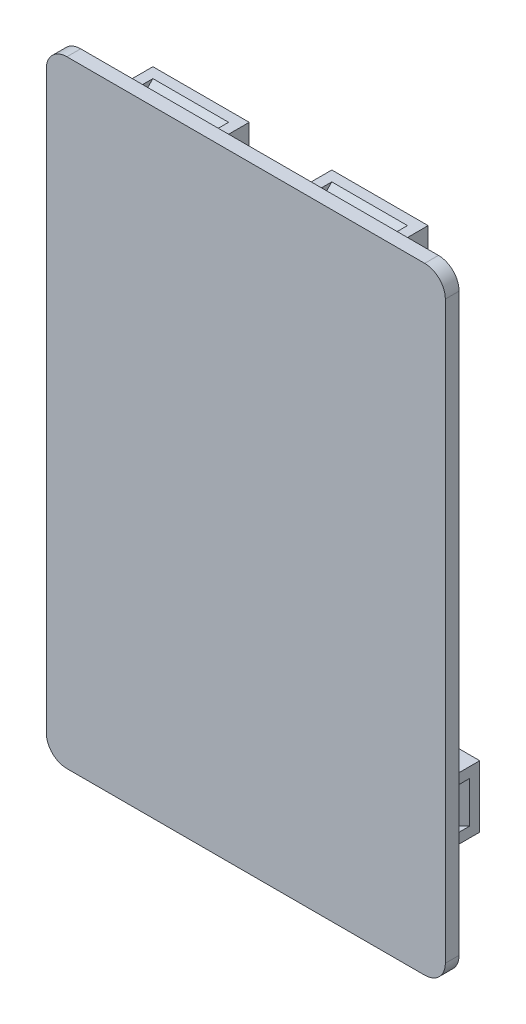
SolidWorks part; units mm, degrees
ref_plane "前视基准面" through (0, 0, 0) normal (0, 0, 1) x (1, 0, 0)
ref_plane "上视基准面" through (0, 0, 0) normal (0, 1, 0) x (1, 0, 0)
ref_plane "右视基准面" through (0, 0, 0) normal (1, 0, 0) x (0, 0, -1)
other "Configuration Table"
sketch "草图2" plane through (0, 0, 0) normal (0, 0, 1) x (1, 0, 0)
  line L4 (0, 86.6) -> (0, 3)
  line L5 (3, 0) -> (55, 0)
  line L6 (58, 3) -> (58, 86.6)
  line L7 (55, 89.6) -> (3, 89.6)
  line L8 (0, 86.6) -> (0, 3)
  line L9 (3, 0) -> (55, 0)
  line L10 (58, 3) -> (58, 86.6)
  line L11 (55, 89.6) -> (3, 89.6)
  arc A4 (3, 89.6) -> (0, 86.6) centre (3, 86.6) ccw
  arc A5 (0, 3) -> (3, 0) centre (3, 3) ccw
  arc A6 (55, 0) -> (58, 3) centre (55, 3) ccw
  arc A7 (58, 86.6) -> (55, 89.6) centre (55, 86.6) ccw
  arc A8 (3, 89.6) -> (0, 86.6) centre (3, 86.6) ccw
  arc A9 (0, 3) -> (3, 0) centre (3, 3) ccw
  arc A10 (55, 0) -> (58, 3) centre (55, 3) ccw
  arc A11 (58, 86.6) -> (55, 89.6) centre (55, 86.6) ccw
  dimension "D1" = 0
extrude "凸台-拉伸1" add sketch "草图2" along normal blind 2
ref_plane "基准面1" through (3, 89.6, 2) normal (-1, 0, 0) x (0, 0, 1)
sketch "草图4" plane through (0, 0, 0) normal (0, 0, -1) x (-1, 0, 0)
  line L0 (-29, 89.6) -> (-29, 0) construction
  line L4 (-3, 89.6) -> (-55, 89.6)
  line L5 (-58, 86.6) -> (-58, 3)
  line L6 (-55, 0) -> (-3, 0)
  line L7 (0, 3) -> (0, 86.6)
  line L8 (-3, 89.6) -> (-55, 89.6)
  line L9 (-58, 86.6) -> (-58, 3)
  line L10 (-55, 0) -> (-3, 0)
  line L11 (0, 3) -> (0, 86.6)
  line L17 (-47.5, 88.1) -> (-49, 88.1)
  line L26 (-36.5, 86.6) -> (-47.5, 86.6)
  line L27 (-36.5, 86.6) -> (-36.5, 88.1)
  line L28 (-36.5, 88.1) -> (-47.5, 88.1)
  line L29 (-47.5, 86.6) -> (-47.5, 88.1)
  line L34 (-49, 88.1) -> (-49, 85.1)
  line L35 (-49, 85.1) -> (-35, 85.1)
  line L36 (-35, 85.1) -> (-35, 88.1)
  line L37 (-35, 88.1) -> (-36.5, 88.1)
  line L38 (-10.5, 88.1) -> (-9, 88.1)
  line L39 (-9, 88.1) -> (-9, 85.1)
  line L40 (-9, 85.1) -> (-23, 85.1)
  line L41 (-23, 85.1) -> (-23, 88.1)
  line L42 (-23, 88.1) -> (-21.5, 88.1)
  line L43 (-21.5, 88.1) -> (-10.5, 88.1)
  arc A4 (0, 86.6) -> (-3, 89.6) centre (-3, 86.6) ccw
  arc A5 (-55, 89.6) -> (-58, 86.6) centre (-55, 86.6) ccw
  arc A6 (-58, 3) -> (-55, 0) centre (-55, 3) ccw
  arc A7 (-3, 0) -> (0, 3) centre (-3, 3) ccw
  arc A8 (0, 86.6) -> (-3, 89.6) centre (-3, 86.6) ccw
  arc A9 (-55, 89.6) -> (-58, 86.6) centre (-55, 86.6) ccw
  arc A10 (-58, 3) -> (-55, 0) centre (-55, 3) ccw
  arc A11 (-3, 0) -> (0, 3) centre (-3, 3) ccw
  dimension "D2" = 7.5
  dimension "D3" = 11
  dimension "D4" = 1.5
  dimension "D5" = 1.5
  dimension "D6" = 1.5
  dimension "D7" = 1.5
  dimension "D8" = 1.5
  dimension "D1" = 0
extrude "凸台-拉伸3" add sketch "草图4" along normal blind 4.5 contours L36 L37 L27 L26 L29 L17 L34 L35 | L43 L42 L41 L40 L39 L38 | L29 L26 L27 L28
sketch "草图5" plane through (49, 0, 0) normal (1, 0, 0) x (0, 0, -1)
  line L0 (1.5, 86.6) -> (1.5, 88.1) construction
  line L1 (3, 88.1) -> (3, 85.1)
  line L2 (3, 86.6) -> (0, 86.6)
  line L3 (1.5, 86.6) -> (0, 88.1)
  line L4 (0, 88.1) -> (0, 85.1)
  line L5 (0, 85.1) -> (4.5, 85.1)
  line L6 (4.5, 85.1) -> (4.5, 88.1)
  line L7 (4.5, 88.1) -> (0, 88.1)
  line L8 (0, 88.1) -> (0, 85.1)
  line L9 (0, 85.1) -> (4.5, 85.1)
  line L10 (4.5, 85.1) -> (4.5, 88.1)
  line L11 (4.5, 88.1) -> (0, 88.1)
  line L12 (3, 88.1) -> (1.5, 86.6)
  line M12 (4.5, 88.1) -> (0, 88.1)
  dimension "D3" = 1.5
  dimension "D1" = 0
extrude "切除-拉伸3" cut sketch "草图5" against normal blind 60 contours L0 L12 M12 | L3 L0 L11
sketch "草图6" plane through (0, 88.1, 0) normal (0, 1, 0) x (1, 0, 0)
  line L0 (35, 4.5) -> (35, 3) construction
  line L1 (35, 3) -> (35, 1.5) construction
  line L2 (35, 1.5) -> (35, 0) construction
  line L3 (49, 1.5) -> (49, 0) construction
  line L4 (49, 4.5) -> (49, 3) construction
  line L5 (49, 3) -> (49, 1.5) construction
  line L6 (35, 4.5) -> (49, 4.5) construction
  line L7 (55, 0) -> (3, 0) construction
  line L8 (9, 4.5) -> (9, 3) construction
  line L9 (23, 4.5) -> (9, 4.5) construction
  line L10 (23, 4.5) -> (23, 3) construction
  line L11 (23, 1.5) -> (23, 0) construction
  line L12 (23, 3) -> (23, 1.5) construction
  line L13 (9, 1.5) -> (9, 3) construction
  line L14 (9, 0) -> (9, 1.5) construction
  line L15 (35, 4.5) -> (35, 3)
  line L16 (35, 3) -> (35, 1.5)
  line L17 (35, 1.5) -> (35, 0)
  line L18 (49, 1.5) -> (49, 0)
  line L19 (49, 4.5) -> (49, 3)
  line L20 (49, 3) -> (49, 1.5)
  line L21 (35, 4.5) -> (49, 4.5)
  line L22 (55, 0) -> (3, 0)
  line L23 (9, 4.5) -> (9, 3)
  line L24 (23, 4.5) -> (9, 4.5)
  line L25 (23, 4.5) -> (23, 3)
  line L26 (23, 1.5) -> (23, 0)
  line L27 (23, 3) -> (23, 1.5)
  line L28 (9, 1.5) -> (9, 3)
  line L29 (9, 0) -> (9, 1.5)
  line L31 (9, 4.5) -> (10.5, 4.5)
  line L32 (9, 4.5) -> (9, 0)
  line L33 (9, 0) -> (10.5, 0)
  line L34 (10.5, 4.5) -> (10.5, 0)
  line L35 (23, 4.5) -> (21.5, 4.5)
  line L36 (23, 4.5) -> (23, 0)
  line L37 (23, 0) -> (21.5, 0)
  line L38 (21.5, 4.5) -> (21.5, 0)
  line L39 (35, 4.5) -> (36.5, 4.5)
  line L40 (35, 4.5) -> (35, 0)
  line L41 (35, 0) -> (36.5, 0)
  line L42 (36.5, 4.5) -> (36.5, 0)
  line L43 (49, 4.5) -> (47.5, 4.5)
  line L44 (49, 4.5) -> (49, 0)
  line L45 (49, 0) -> (47.5, 0)
  line L46 (47.5, 4.5) -> (47.5, 0)
  line M12 (35, 3) -> (49, 3)
  line M13 (49, 3) -> (49, 4.5)
  line M14 (49, 4.5) -> (35, 4.5)
  line M15 (35, 4.5) -> (35, 3)
  dimension "D1" = 1.5
  dimension "D2" = 1.5
  dimension "D3" = 1.5
  dimension "D4" = 1.5
extrude "凸台-拉伸4" add sketch "草图6" against normal blind 1.5 contours L34 L24 L23 L28 L29 L22 | L24 L38 L22 L26 L27 L25 | L42 L21 M15 M12 | L42 L16 L17 L22 M12 | L46 L22 L18 L20 M12 | L46 M14 M12 M13
sketch "草图8" plane through (0, 0, 0) normal (0, 0, -1) x (-1, 0, 0)
  line L0 (-56.5, 17) -> (-56.5, 15.5)
  line L1 (-55, 17) -> (-56.5, 17)
  line L2 (-55, 17) -> (-55, 23)
  line L3 (-55, 23) -> (-56.5, 23)
  line L4 (0, 3) -> (0, 86.6)
  line L5 (-3, 89.6) -> (-55, 89.6)
  line L6 (-58, 86.6) -> (-58, 3)
  line L7 (-55, 0) -> (-3, 0)
  line L8 (0, 3) -> (0, 86.6)
  line L9 (-3, 89.6) -> (-55, 89.6)
  line L10 (-58, 86.6) -> (-58, 3)
  line L11 (-55, 0) -> (-3, 0)
  line L12 (-56.5, 17) -> (-56.5, 23)
  line L17 (-56.5, 15.5) -> (-53.5, 15.5)
  line L18 (-53.5, 15.5) -> (-53.5, 24.5)
  line L19 (-53.5, 24.5) -> (-56.5, 24.5)
  line L20 (-56.5, 24.5) -> (-56.5, 23)
  line L21 (-29, 179.2) -> (-29, 0)
  line L22 (-1.5, 15.5) -> (-4.5, 15.5)
  line L23 (-1.5, 17) -> (-1.5, 15.5)
  line L24 (-1.5, 17) -> (-1.5, 23)
  line L25 (-1.5, 24.5) -> (-1.5, 23)
  line L26 (-4.5, 24.5) -> (-1.5, 24.5)
  line L27 (-4.5, 15.5) -> (-4.5, 24.5)
  arc A4 (0, 86.6) -> (-3, 89.6) centre (-3, 86.6) ccw
  arc A5 (-55, 89.6) -> (-58, 86.6) centre (-55, 86.6) ccw
  arc A6 (-58, 3) -> (-55, 0) centre (-55, 3) ccw
  arc A7 (-3, 0) -> (0, 3) centre (-3, 3) ccw
  arc A8 (0, 86.6) -> (-3, 89.6) centre (-3, 86.6) ccw
  arc A9 (-55, 89.6) -> (-58, 86.6) centre (-55, 86.6) ccw
  arc A10 (-58, 3) -> (-55, 0) centre (-55, 3) ccw
  arc A11 (-3, 0) -> (0, 3) centre (-3, 3) ccw
  point P23 (-29, 89.6)
  dimension "D2" = 17
  dimension "D3" = 6
  dimension "D4" = 1.5
  dimension "D5" = 1.5
  dimension "D6" = 1.5
  dimension "D7" = 1.5
  dimension "D8" = 1.5
  dimension "D1" = 0
extrude "凸台-拉伸5" add sketch "草图8" along normal blind 4.5 contours L19 L20 L3 L2 L1 L0 L17 L18 | L12 L1 L2 L3 | L27 L22 L23 L24 L25 L26
sketch "草图9" plane through (0, 15.5, 0) normal (0, -1, 0) x (1, 0, 0)
  line L0 (56.5, 0) -> (53.5, 0) construction
  line L1 (53.5, 0) -> (53.5, -4.5) construction
  line L2 (53.5, -4.5) -> (56.5, -4.5) construction
  line L3 (56.5, -4.5) -> (56.5, 0) construction
  line L4 (4.5, 0) -> (1.5, 0) construction
  line L5 (1.5, 0) -> (1.5, -4.5) construction
  line L6 (1.5, -4.5) -> (4.5, -4.5) construction
  line L7 (4.5, -4.5) -> (4.5, 0) construction
  line L8 (56.5, 0) -> (53.5, 0)
  line L9 (53.5, 0) -> (53.5, -4.5)
  line L10 (53.5, -4.5) -> (56.5, -4.5)
  line L11 (56.5, -4.5) -> (56.5, 0)
  line L12 (4.5, 0) -> (1.5, 0)
  line L13 (1.5, 0) -> (1.5, -4.5)
  line L14 (1.5, -4.5) -> (4.5, -4.5)
  line L15 (4.5, -4.5) -> (4.5, 0)
  line L16 (1.5, -3) -> (4.5, -3)
  line L17 (3, 0) -> (3, -3)
  line L18 (3, -1.5) -> (4.5, -1.5) construction
  line L19 (4.5, 0) -> (3, -1.5)
  line L20 (3, -1.5) -> (4.5, -3)
  line L21 (55, 0) -> (55, -4.5)
  line L22 (53.5, -3) -> (55, -3)
  line L23 (55, -1.5) -> (53.5, -1.5) construction
  line L24 (53.5, 0) -> (55, -1.5)
  line L25 (55, -1.5) -> (53.5, -3)
  line L26 (3, -1.5) -> (1.5, 0)
  line L27 (1.5, -3) -> (3, -1.5)
  line L28 (56.5, 0) -> (55, -1.5)
  line L29 (55, -3) -> (56.5, -3)
  line L30 (55, -1.5) -> (56.5, -3)
  dimension "D1" = 1.5
  dimension "D2" = 1.5
  dimension "D3" = 1.5
  dimension "D4" = 1.5
extrude "切除-拉伸4" cut sketch "草图9" against normal blind 20 contours L13 L27 L26 | L28 L30 L11
sketch "草图12" plane through (1.5, 0, 0) normal (-1, 0, 0) x (0, 0, 1)
  line L0 (0, 24.5) -> (-1.5, 24.5) construction
  line L1 (-1.5, 15.5) -> (0, 15.5) construction
  line L2 (0, 15.5) -> (0, 24.5) construction
  line L3 (-1.5, 24.5) -> (-3, 24.5) construction
  line L4 (-3, 15.5) -> (-1.5, 15.5) construction
  line L5 (-3, 24.5) -> (-4.5, 24.5) construction
  line L6 (-4.5, 24.5) -> (-4.5, 15.5) construction
  line L7 (-4.5, 15.5) -> (-3, 15.5) construction
  line L8 (0, 24.5) -> (-1.5, 24.5)
  line L9 (-1.5, 15.5) -> (0, 15.5)
  line L10 (0, 15.5) -> (0, 24.5)
  line L11 (-1.5, 24.5) -> (-3, 24.5)
  line L12 (-3, 15.5) -> (-1.5, 15.5)
  line L13 (-3, 24.5) -> (-4.5, 24.5)
  line L14 (-4.5, 24.5) -> (-4.5, 15.5)
  line L15 (-4.5, 15.5) -> (-3, 15.5)
  line L17 (-4.5, 24.5) -> (0, 24.5)
  line L18 (-4.5, 24.5) -> (-4.5, 23)
  line L19 (-4.5, 23) -> (0, 23)
  line L20 (0, 24.5) -> (0, 23)
  line L21 (0, 15.5) -> (-4.5, 15.5)
  line L22 (0, 15.5) -> (0, 17)
  line L23 (0, 17) -> (-4.5, 17)
  line L24 (-4.5, 15.5) -> (-4.5, 17)
  line M5 (-3, 15.5) -> (-3, 24.5)
  line M6 (-3, 24.5) -> (-4.5, 24.5)
  line M7 (-4.5, 24.5) -> (-4.5, 15.5)
  line M8 (-4.5, 15.5) -> (-3, 15.5)
  dimension "D1" = 1.5
  dimension "D2" = 1.5
extrude "凸台-拉伸7" add sketch "草图12" against normal blind 1.5 contours L19 L10 L8 L11 M5 | L10 L23 L12 L9 M5 | L19 M7 M5 M6 | L23 M5 M7 M8
sketch "草图13" plane through (56.5, 0, 0) normal (1, 0, 0) x (0, 0, -1)
  line L0 (0, 24.5) -> (0, 15.5) construction
  line L1 (0, 15.5) -> (1.5, 15.5) construction
  line L2 (1.5, 24.5) -> (0, 24.5) construction
  line L3 (1.5, 15.5) -> (3, 15.5) construction
  line L4 (3, 24.5) -> (1.5, 24.5) construction
  line L5 (4.5, 24.5) -> (3, 24.5) construction
  line L6 (3, 15.5) -> (4.5, 15.5) construction
  line L7 (4.5, 15.5) -> (4.5, 24.5) construction
  line L8 (0, 24.5) -> (0, 15.5)
  line L9 (0, 15.5) -> (1.5, 15.5)
  line L10 (1.5, 24.5) -> (0, 24.5)
  line L11 (1.5, 15.5) -> (3, 15.5)
  line L12 (3, 24.5) -> (1.5, 24.5)
  line L13 (4.5, 24.5) -> (3, 24.5)
  line L14 (3, 15.5) -> (4.5, 15.5)
  line L15 (4.5, 15.5) -> (4.5, 24.5)
  line L17 (0, 24.5) -> (4.5, 24.5)
  line L18 (0, 24.5) -> (0, 23)
  line L19 (0, 23) -> (4.5, 23)
  line L20 (4.5, 24.5) -> (4.5, 23)
  line L21 (4.5, 15.5) -> (0, 15.5)
  line L22 (4.5, 15.5) -> (4.5, 17)
  line L23 (4.5, 17) -> (0, 17)
  line L24 (0, 15.5) -> (0, 17)
  line M11 (4.5, 24.5) -> (3, 24.5)
  line M12 (3, 24.5) -> (3, 15.5)
  line M13 (3, 15.5) -> (4.5, 15.5)
  line M14 (4.5, 15.5) -> (4.5, 24.5)
  dimension "D1" = 1.5
  dimension "D2" = 1.5
extrude "凸台-拉伸8" add sketch "草图13" against normal blind 1.5 contours L23 M14 M12 M13 | L23 L8 L9 L11 M12 | L19 L15 M12 M11 | L8 L19 L12 L10 M12
